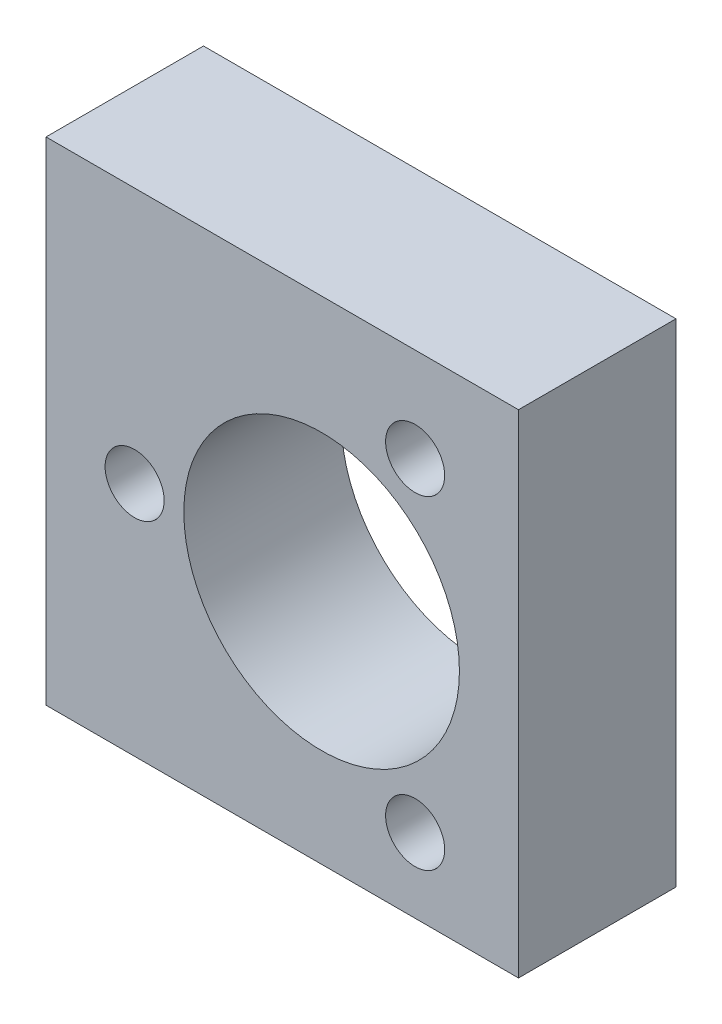
SolidWorks part; units mm, degrees
ref_plane "Front" through (0, 0, 0) normal (0, 0, 1) x (1, 0, 0)
ref_plane "Top" through (0, 0, 0) normal (0, 1, 0) x (1, 0, 0)
ref_plane "Right" through (0, 0, 0) normal (1, 0, 0) x (0, 0, -1)
sketch "Esquisse1" plane through (0, 0, 0) normal (0, 0, 1) x (1, 0, 0)
  line L0 (0, 12) -> (24, 12) construction
  line L1 (0, 0) -> (24, 0)
  line L2 (0, 0) -> (0, 25)
  line L3 (0, 25) -> (24, 25)
  line L4 (24, 0) -> (24, 25)
  line L5 (14, 12) -> (14, 19) construction
  line L6 (14, 12) -> (4.5, 12) construction
  line L7 (14, 12) -> (18.75, 20.2272) construction
  circle A0 centre (14, 12) radius 7
  circle A1 centre (4.5, 12) radius 1.5
  circle A2 centre (18.75, 20.2272) radius 1.5
  circle A3 centre (18.75, 3.7728) radius 1.5
  dimension "D3" = 14
  dimension "D5" = 3
  dimension "D6" = 9.5
  dimension "D1" = 24
  dimension "D2" = 25
  dimension "D4" = 12
  dimension "D8" = 120
  dimension "D9" = 14
  dimension "D7" = 3
extrude "Boss.-Extru.1" add sketch "Esquisse1" along normal blind 8
